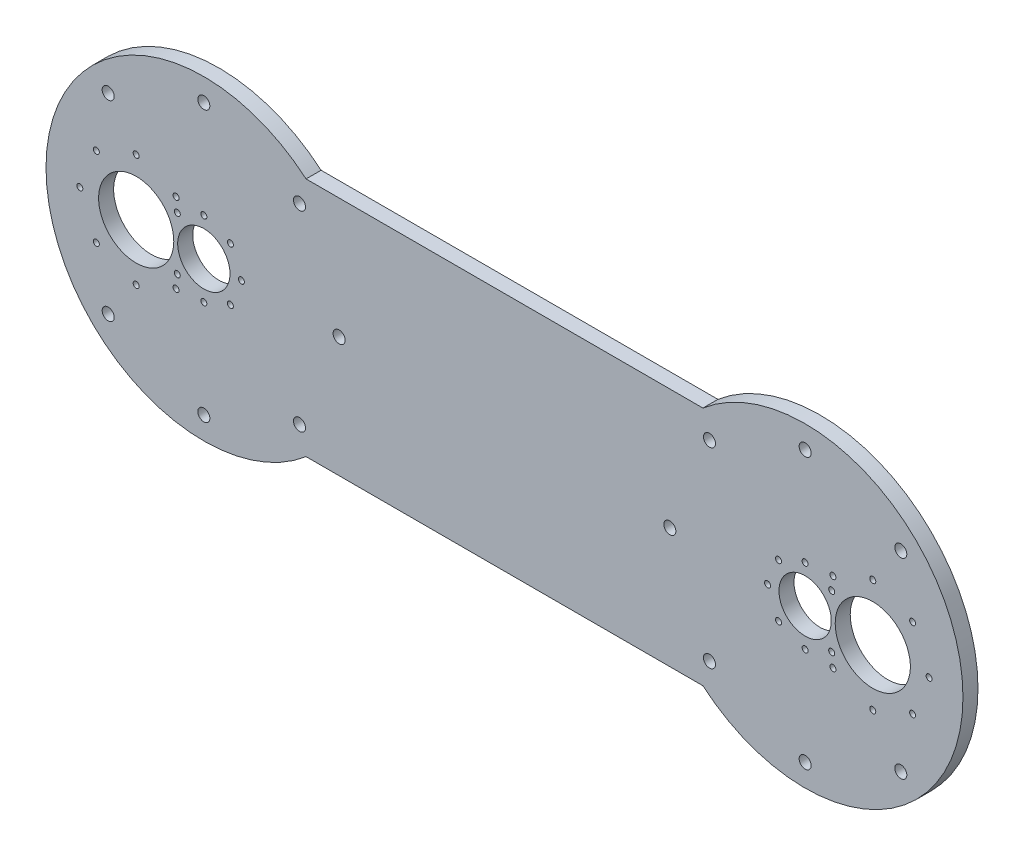
SolidWorks part; units mm, degrees
material "ABS"
ref_plane "Front Plane" through (0, 0, 0) normal (0, 0, 1) x (1, 0, 0)
ref_plane "Top Plane" through (0, 0, 0) normal (0, 1, 0) x (1, 0, 0)
ref_plane "Right Plane" through (0, 0, 0) normal (1, 0, 0) x (0, 0, -1)
sketch "Sketch1" plane through (0, 0, 0) normal (0, 0, 1) x (1, 0, 0)
  line L0 (-87.4716, -41.275) -> (87.4716, -41.275) construction
  line L1 (-83.8153, 50.8) -> (83.8153, 50.8)
  line L2 (-87.4716, 41.275) -> (87.4716, 41.275) construction
  line L3 (-83.8153, -50.8) -> (83.8153, -50.8)
  line L4 (0, 0) -> (0, 100.7987) construction
  arc A0 (-87.4716, 41.275) -> (-87.4716, -41.275) centre (-127, 0) ccw construction
  arc A1 (87.4716, -41.275) -> (87.4716, 41.275) centre (127, 0) ccw construction
  circle A2 centre (-127, 0) radius 3.175
  circle A3 centre (127, 0) radius 3.175
  arc A4 (-83.8153, 50.8) -> (-83.8153, -50.8) centre (-127, 0) ccw
  arc A5 (83.8153, -50.8) -> (83.8153, 50.8) centre (127, 0) ccw
  circle A6 centre (-127, 57.15) radius 2.54
  circle A7 centre (-86.5888, 40.4112) radius 2.54
  circle A8 centre (-69.85, 0) radius 2.54
  circle A9 centre (-86.5888, -40.4112) radius 2.54
  circle A10 centre (-127, -57.15) radius 2.54
  circle A11 centre (-167.4112, -40.4112) radius 2.54
  circle A12 centre (-184.15, 0) radius 2.54 [skipped]
  circle A13 centre (-167.4112, 40.4112) radius 2.54
  circle A14 centre (127, 57.15) radius 2.54
  circle A15 centre (167.4112, 40.4112) radius 2.54
  circle A16 centre (167.4112, -40.4112) radius 2.54
  circle A17 centre (127, -57.15) radius 2.54
  circle A18 centre (86.5888, -40.4112) radius 2.54
  circle A19 centre (69.85, 0) radius 2.54
  circle A20 centre (86.5888, 40.4112) radius 2.54
  point P0 (0, 0)
  dimension "D3" = 6.35
  dimension "D4" = 6.35
  dimension "D6" = 133.35
  dimension "D7" = 133.35
  dimension "D2" = 5.08
  dimension "D5" = 8
  dimension "D1" = 9.525
extrude "Boss-Extrude1" add sketch "Sketch1" along normal mid plane 6.35
sketch "Sketch2" plane through (0, 0, 3.175) normal (0, 0, 1) x (1, 0, 0)
  line L0 (-127, 0) -> (-207.737, 0) construction
  line L4 (0, 0) -> (0, 93.9723) construction
  circle A0 centre (-127, 0) radius 11.049
  circle A1 centre (-155.575, 0) radius 15.875
  circle A2 centre (127, 0) radius 15.875 construction
  circle A3 centre (155.575, 0) radius 23.8125 construction
  circle A4 centre (-155.575, 0) radius 23.8125 construction
  circle A5 centre (-127, 0) radius 15.875 construction
  circle A6 centre (-155.575, 23.8125) radius 1.27
  circle A7 centre (-138.737, 16.838) radius 1.27
  circle A8 centre (-131.7625, 0) radius 1.27 [skipped]
  circle A9 centre (-138.737, -16.838) radius 1.27
  circle A10 centre (-155.575, -23.8125) radius 1.27
  circle A11 centre (-172.413, -16.838) radius 1.27
  circle A12 centre (-179.3875, 0) radius 1.27
  circle A13 centre (-172.413, 16.838) radius 1.27
  circle A14 centre (-127, 15.875) radius 1.27
  circle A15 centre (-115.7747, 11.2253) radius 1.27
  circle A16 centre (-111.125, 0) radius 1.27
  circle A17 centre (-115.7747, -11.2253) radius 1.27
  circle A18 centre (-127, -15.875) radius 1.27
  circle A19 centre (-138.2253, -11.2253) radius 1.27
  circle A20 centre (138.2253, 11.2253) radius 1.27
  circle A21 centre (-138.2253, 11.2253) radius 1.27
  circle A22 centre (-142.875, 0) radius 1.27 [skipped]
  circle A23 centre (138.2253, -11.2253) radius 1.27
  circle A24 centre (127, -15.875) radius 1.27
  circle A25 centre (115.7747, -11.2253) radius 1.27
  circle A26 centre (111.125, 0) radius 1.27
  circle A27 centre (115.7747, 11.2253) radius 1.27
  circle A28 centre (127, 15.875) radius 1.27
  circle A29 centre (172.413, 16.838) radius 1.27
  circle A30 centre (179.3875, 0) radius 1.27
  circle A31 centre (172.413, -16.838) radius 1.27
  circle A32 centre (155.575, -23.8125) radius 1.27
  circle A33 centre (138.737, -16.838) radius 1.27
  circle A34 centre (138.737, 16.838) radius 1.27
  circle A35 centre (155.575, 23.8125) radius 1.27
  circle A36 centre (155.575, 0) radius 15.875
  circle A37 centre (127, 0) radius 11.049
  dimension "D2" = 28.575
  dimension "D3" = 31.75
  dimension "D4" = 31.75
  dimension "D5" = 47.625
  dimension "D6" = 2.54
  dimension "D1" = 22.098
  dimension "D8" = 2.54
  dimension "D7" = 8
  dimension "D9" = 8
extrude "Cut-Extrude1" cut sketch "Sketch2" against normal through all
